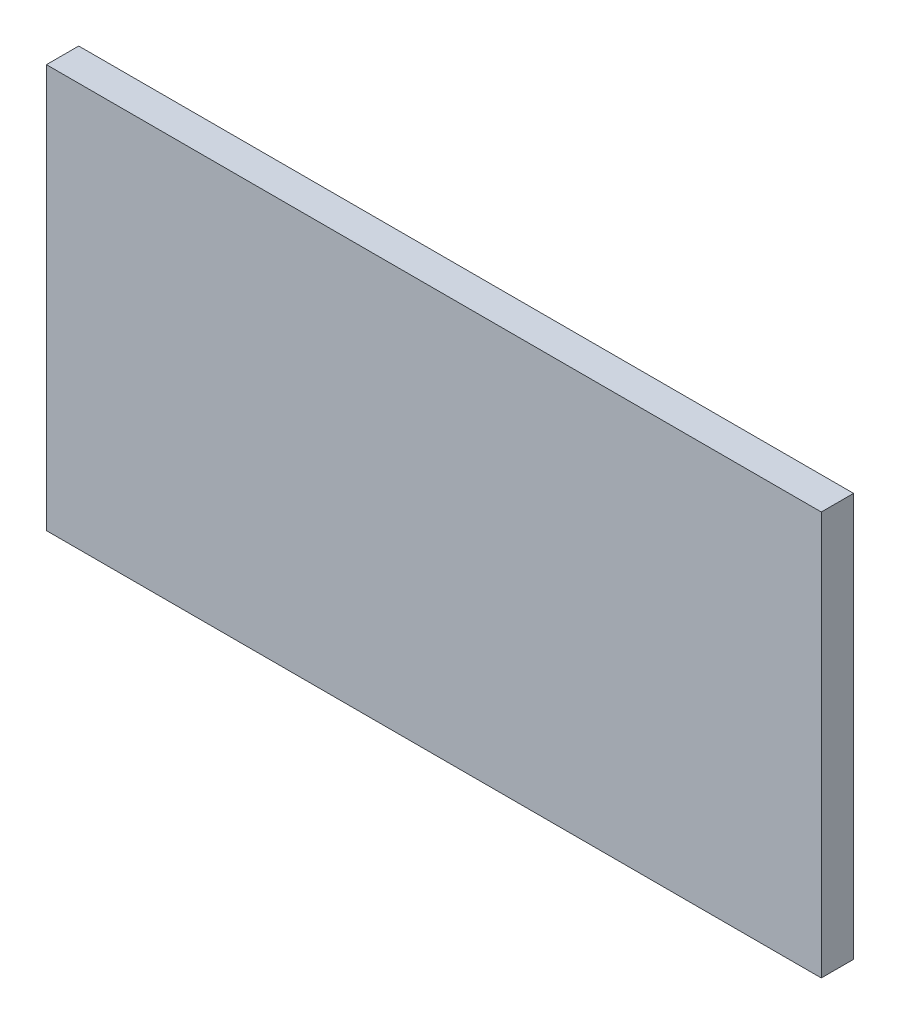
SolidWorks part; units mm, degrees
ref_plane "Front Plane" through (0, 0, 0) normal (0, 0, 1) x (1, 0, 0)
ref_plane "Top Plane" through (0, 0, 0) normal (0, 1, 0) x (1, 0, 0)
ref_plane "Right Plane" through (0, 0, 0) normal (1, 0, 0) x (0, 0, -1)
sketch "Sketch2" plane through (-46.9085, 0, 0) normal (0, 0, 1) x (1, 0, 0)
  line L1 (234.8028, 362.6785) -> (1454.0028, 362.6785)
  line L2 (234.8028, 362.6785) -> (234.8028, 997.6785)
  line L3 (234.8028, 997.6785) -> (1454.0028, 997.6785)
  line L4 (1454.0028, 362.6785) -> (1454.0028, 997.6785)
  dimension "D1" = 1219.2
  dimension "D2" = 635
extrude "Boss-Extrude1" add sketch "Sketch2" against normal blind 50.8
